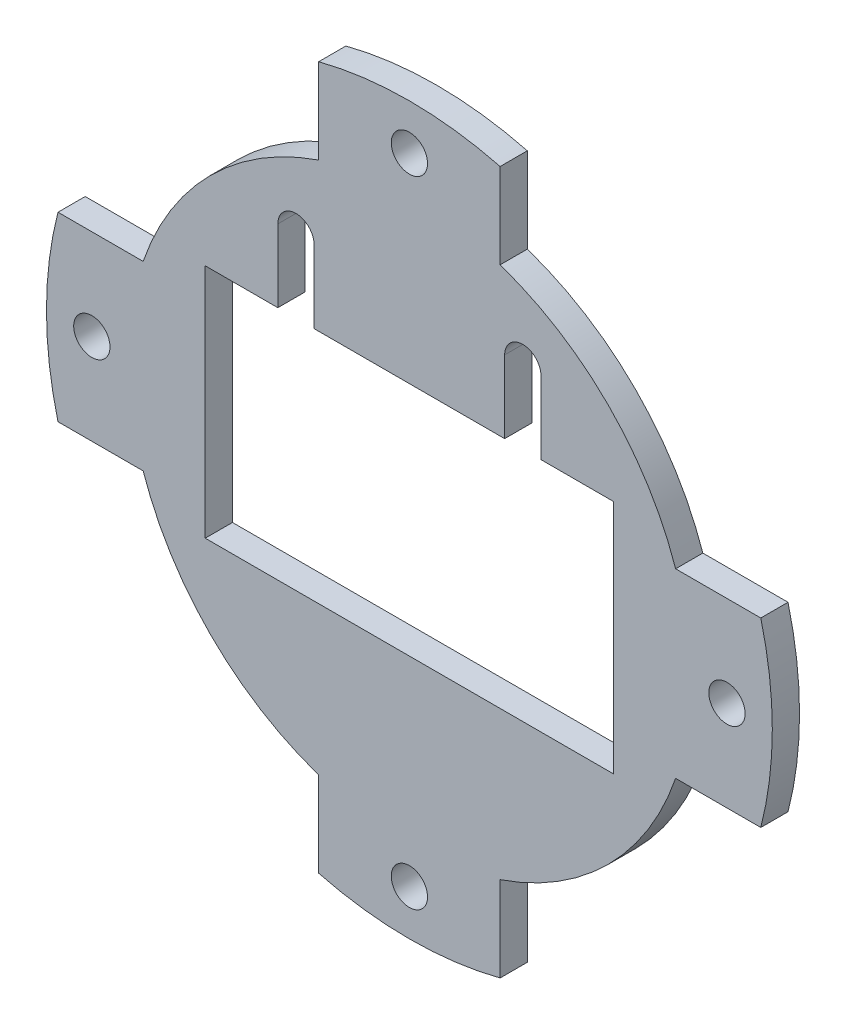
SolidWorks part; units mm, degrees
ref_plane "Front Plane" through (0, 0, 0) normal (0, 0, 1) x (1, 0, 0)
ref_plane "Top Plane" through (0, 0, 0) normal (0, 1, 0) x (1, 0, 0)
ref_plane "Right Plane" through (0, 0, 0) normal (1, 0, 0) x (0, 0, -1)
sketch "Sketch1" plane through (0, 0, 0) normal (0, 0, 1) x (1, 0, 0)
  line L0 (0, 31) -> (0, 40) construction
  line L1 (10, 29.3428) -> (10, 38.7298)
  line L2 (-10, 29.3428) -> (-10, 38.7298)
  line L5 (10, 0) -> (10, 40) construction
  line L6 (0, 0) -> (0, 40) construction
  line L7 (-10, 0) -> (-10, 40) construction
  line L8 (29.3428, 10) -> (38.7298, 10)
  line L9 (29.3428, -10) -> (38.7298, -10)
  line L10 (10, -29.3428) -> (10, -38.7298)
  line L11 (-10, -29.3428) -> (-10, -38.7298)
  line L12 (-29.3428, -10) -> (-38.7298, -10)
  line L13 (-29.3428, 10) -> (-38.7298, 10)
  arc A0 (10, 38.7298) -> (-10, 38.7298) centre (0, 0) ccw
  arc A2 (-10, 29.3428) -> (-29.3428, 10) centre (0, 0) ccw
  arc A3 (38.7298, -10) -> (38.7298, 10) centre (0, 0) ccw
  arc A4 (-10, -38.7298) -> (10, -38.7298) centre (0, 0) ccw
  arc A5 (-38.7298, 10) -> (-38.7298, -10) centre (0, 0) ccw
  arc A6 (-29.3428, -10) -> (-10, -29.3428) centre (0, 0) ccw
  arc A7 (29.3428, 10) -> (10, 29.3428) centre (0, 0) ccw
  arc A8 (10, -29.3428) -> (29.3428, -10) centre (0, 0) ccw
  point P27 (0, 0)
  dimension "D1" = 80
  dimension "D3" = 10
  dimension "D4" = 10
extrude "Boss-Extrude1" add sketch "Sketch1" along normal blind 3
sketch "Sketch2" plane through (0, 0, 3) normal (0, 0, 1) x (1, 0, 0)
  line L1 (22.5, 13) -> (-22.5, 13)
  line L2 (22.5, 13) -> (22.5, -13)
  line L3 (22.5, -13) -> (-22.5, -13)
  line L4 (-22.5, 13) -> (-22.5, -13)
  line L5 (22.5, 13) -> (-22.5, -13) construction
  line L6 (22.5, -13) -> (-22.5, 13) construction
  point P0 (0, 0)
  dimension "D1" = 45
  dimension "D2" = 26
extrude "Cut-Extrude1" cut sketch "Sketch2" against normal up to next
sketch "Sketch3" plane through (0, 0, 3) normal (0, 0, 1) x (1, 0, 0)
  line L0 (0, 0) -> (0, 40) construction
  line L1 (4.9006, 21) -> (-14.3438, 21) construction
  line L2 (22.5, 13) -> (-22.5, 13) construction
  line L3 (-10.5, 21) -> (-10.5, 13)
  line L4 (10.5, 21) -> (10.5, 13)
  line L5 (-14.5, 21) -> (-14.5, 13)
  line L6 (14.5, 21) -> (14.5, 13)
  line L7 (14.5, 13) -> (10.5, 13)
  line L8 (-14.5, 13) -> (-10.5, 13)
  arc A0 (10, 38.7298) -> (-10, 38.7298) centre (0, 0) ccw construction
  arc A1 (-10.5, 21) -> (-14.5, 21) centre (-12.5, 21) ccw
  arc A2 (10.5, 21) -> (14.5, 21) centre (12.5, 21) cw
  dimension "D1" = 25
  dimension "D2" = 4
  dimension "D3" = 8
extrude "Cut-Extrude2" cut sketch "Sketch3" against normal up to next
sketch "Sketch4" plane through (0, 0, 3) normal (0, 0, 1) x (1, 0, 0)
  line L0 (0, 0) -> (0, 40) construction
  arc A0 (10, 38.7298) -> (-10, 38.7298) centre (0, 0) ccw construction
  circle A1 centre (0, 35) radius 2
  circle A2 centre (35, 0) radius 2
  circle A3 centre (0, -35) radius 2
  circle A4 centre (-35, 0) radius 2
  point P17 (0, 0)
  dimension "D1" = 35
  dimension "D2" = 4
extrude "Cut-Extrude3" cut sketch "Sketch4" against normal blind 10
